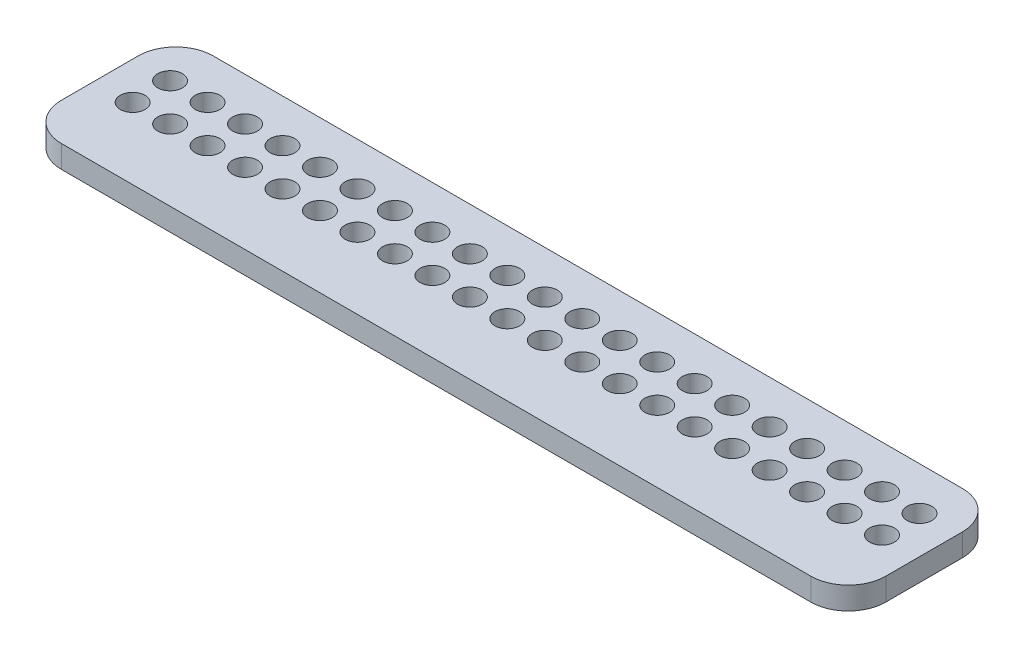
SolidWorks part; units mm, degrees
ref_plane "Front Plane" through (0, 0, 0) normal (0, 0, 1) x (1, 0, 0)
ref_plane "Top Plane" through (0, 0, 0) normal (0, 1, 0) x (1, 0, 0)
ref_plane "Right Plane" through (0, 0, 0) normal (1, 0, 0) x (0, 0, -1)
sketch "Sketch1" plane through (0, 0, 0) normal (0, 1, 0) x (1, 0, 0)
  line L1 (-57.4318, 14.3884) -> (42.5682, 14.3884)
  line L2 (-62.4318, 19.3884) -> (-62.4318, 29.6384)
  line L3 (-57.4318, 34.6384) -> (42.5682, 34.6384)
  line L4 (47.5682, 19.3884) -> (47.5682, 29.6384)
  circle A0 centre (-57.4318, 28.8884) radius 1.65
  arc A1 (42.5682, 34.6384) -> (47.5682, 29.6384) centre (42.5682, 29.6384) cw
  arc A2 (42.5682, 14.3884) -> (47.5682, 19.3884) centre (42.5682, 19.3884) ccw
  arc A3 (-57.4318, 14.3884) -> (-62.4318, 19.3884) centre (-57.4318, 19.3884) cw
  arc A4 (-62.4318, 29.6384) -> (-57.4318, 34.6384) centre (-57.4318, 29.6384) cw
  circle A5 centre (-52.4318, 28.8884) radius 1.65
  circle A6 centre (-47.4318, 28.8884) radius 1.65
  circle A7 centre (-42.4318, 28.8884) radius 1.65
  circle A8 centre (-37.4318, 28.8884) radius 1.65
  circle A9 centre (-32.4318, 28.8884) radius 1.65
  circle A10 centre (-27.4318, 28.8884) radius 1.65
  circle A11 centre (-22.4318, 28.8884) radius 1.65
  circle A12 centre (-17.4318, 28.8884) radius 1.65
  circle A13 centre (-12.4318, 28.8884) radius 1.65
  circle A14 centre (-7.4318, 28.8884) radius 1.65
  circle A15 centre (-2.4318, 28.8884) radius 1.65
  circle A16 centre (2.5682, 28.8884) radius 1.65
  circle A17 centre (7.5682, 28.8884) radius 1.65
  circle A18 centre (12.5682, 28.8884) radius 1.65
  circle A19 centre (17.5682, 28.8884) radius 1.65
  circle A20 centre (22.5682, 28.8884) radius 1.65
  circle A21 centre (27.5682, 28.8884) radius 1.65
  circle A22 centre (32.5682, 28.8884) radius 1.65
  circle A23 centre (37.5682, 28.8884) radius 1.65
  circle A24 centre (42.5682, 28.8884) radius 1.65
  circle A25 centre (-52.4318, 23.8884) radius 1.65
  circle A26 centre (-47.4318, 23.8884) radius 1.65
  circle A27 centre (-42.4318, 23.8884) radius 1.65
  circle A28 centre (-37.4318, 23.8884) radius 1.65
  circle A29 centre (-32.4318, 23.8884) radius 1.65
  circle A30 centre (-27.4318, 23.8884) radius 1.65
  circle A31 centre (-22.4318, 23.8884) radius 1.65
  circle A32 centre (-17.4318, 23.8884) radius 1.65
  circle A33 centre (-12.4318, 23.8884) radius 1.65
  circle A34 centre (-7.4318, 23.8884) radius 1.65
  circle A35 centre (-2.4318, 23.8884) radius 1.65
  circle A36 centre (2.5682, 23.8884) radius 1.65
  circle A37 centre (7.5682, 23.8884) radius 1.65
  circle A38 centre (12.5682, 23.8884) radius 1.65
  circle A39 centre (17.5682, 23.8884) radius 1.65
  circle A40 centre (22.5682, 23.8884) radius 1.65
  circle A41 centre (27.5682, 23.8884) radius 1.65
  circle A42 centre (32.5682, 23.8884) radius 1.65
  circle A43 centre (37.5682, 23.8884) radius 1.65
  circle A44 centre (42.5682, 23.8884) radius 1.65
  circle A45 centre (-57.4318, 23.8884) radius 1.65
  point P8 (47.5682, 34.6384)
  point P13 (-62.4318, 14.3884)
  point P16 (-62.4318, 34.6384)
  dimension "D3" = 3.3
  dimension "D4" = 5
  dimension "D7" = 5
  dimension "D1" = 5
  dimension "D2" = 20.25
  dimension "D8" = 5.75
  dimension "D5" = 21
  dimension "D6" = 2
extrude "Boss-Extrude1" add sketch "Sketch1" along normal blind 3
